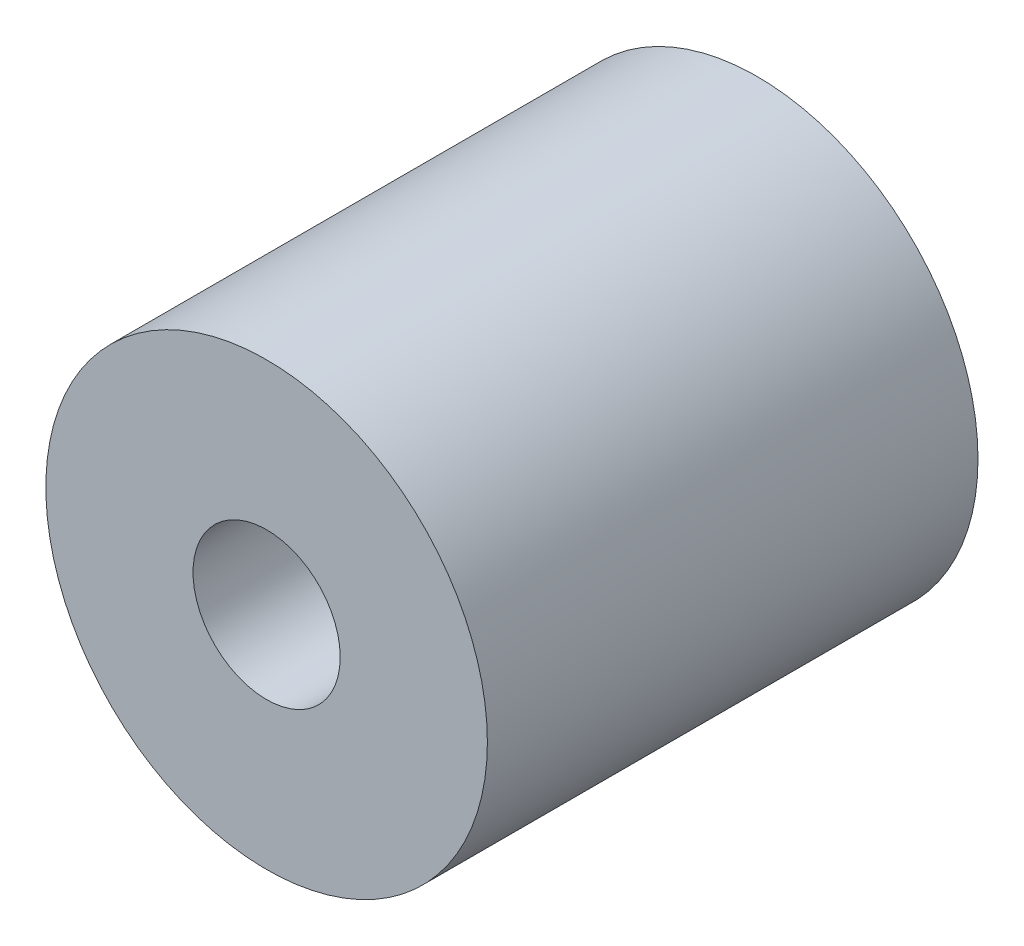
SolidWorks part; units mm, degrees
material "尼龙 101"
ref_plane "前视基准面" through (0, 0, 0) normal (0, 0, 1) x (1, 0, 0)
ref_plane "上视基准面" through (0, 0, 0) normal (0, 1, 0) x (1, 0, 0)
ref_plane "右视基准面" through (0, 0, 0) normal (1, 0, 0) x (0, 0, -1)
sketch "草图1" plane through (0, 0, 0) normal (0, 0, 1) x (1, 0, 0)
  circle A0 centre (0, 0) radius 4.5
  circle A1 centre (0, 0) radius 1.5
  dimension "D1" = 9
  dimension "D2" = 3
extrude "凸台-拉伸1" add sketch "草图1" along normal blind 10
